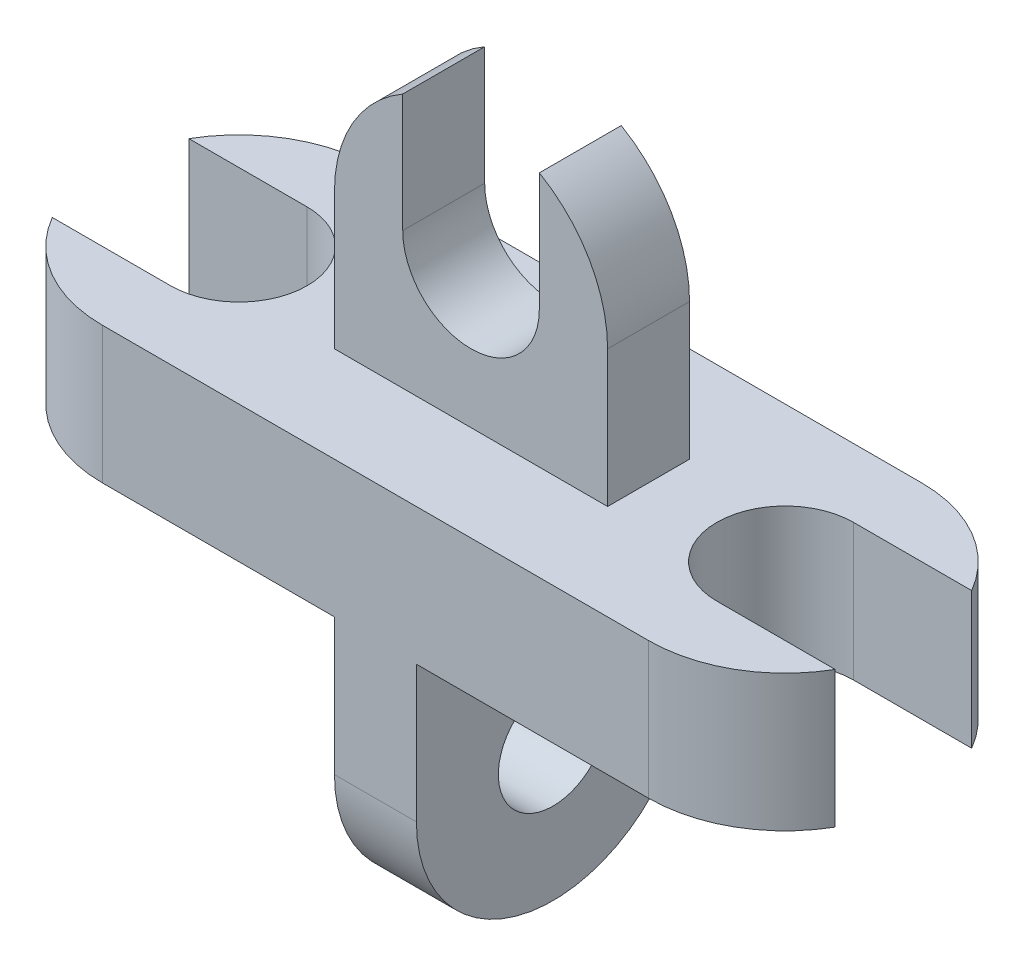
SolidWorks part; units mm, degrees
ref_plane "Front Plane" through (0, 0, 0) normal (0, 0, 1) x (1, 0, 0)
ref_plane "Top Plane" through (0, 0, 0) normal (0, 1, 0) x (1, 0, 0)
ref_plane "Right Plane" through (0, 0, 0) normal (1, 0, 0) x (0, 0, -1)
sketch "Sketch1" plane through (0, 0, 0) normal (0, 1, 0) x (1, 0, 0)
  line L0 (100, 0) -> (-100, 0) construction
  line L1 (100, -50) -> (-100, -50)
  line L2 (100, 50) -> (-100, 50)
  line L3 (-100, 25) -> (-143.3013, 25)
  line L4 (-100, -25) -> (-143.3013, -25)
  line L5 (0, 0) -> (0, 50) construction
  line L6 (100, -25) -> (143.3013, -25)
  line L7 (100, 25) -> (143.3013, 25)
  arc A1 (-100, 50) -> (-143.3013, 25) centre (-100, 0) ccw
  arc A2 (-100, -25) -> (-100, 25) centre (-100, 0) ccw
  arc A4 (-143.3013, -25) -> (-100, -50) centre (-100, 0) ccw
  arc A5 (143.3013, -25) -> (100, -50) centre (100, 0) cw
  arc A6 (100, -25) -> (100, 25) centre (100, 0) cw
  arc A7 (100, 50) -> (143.3013, 25) centre (100, 0) cw
  point P2 (0, 0)
  point P19 (0, 0)
  point P20 (0, 0)
  dimension "D1" = 50
  dimension "D3" = 200
  dimension "D2" = 25
extrude "Boss-Extrude1" add sketch "Sketch1" along normal mid plane 50
sketch "Sketch2" plane through (0, 0, 0) normal (0, 0, 1) x (1, 0, 0)
  line L0 (-100, 25) -> (100, 25) construction
  line L1 (-50, 75) -> (-50, 25)
  line L2 (50, 75) -> (50, 25)
  line L3 (-50, 25) -> (50, 25)
  line L4 (-25, 75) -> (-25, 118.3013)
  line L5 (25, 75) -> (25, 118.3013)
  arc A0 (50, 75) -> (25, 118.3013) centre (0, 75) ccw
  arc A1 (-25, 75) -> (25, 75) centre (0, 75) ccw
  arc A2 (-25, 118.3013) -> (-50, 75) centre (0, 75) ccw
  dimension "D1" = 100
  dimension "D2" = 50
  dimension "D3" = 50
extrude "Boss-Extrude2" add sketch "Sketch2" along normal mid plane 30
sketch "Sketch3" plane through (0, 0, 0) normal (1, 0, 0) x (0, 0, -1)
  line L0 (-50, -25) -> (-25, -25) construction
  line L1 (-50, -75) -> (-50, -25)
  line L2 (50, -75) -> (50, -25)
  line L3 (-50, -25) -> (50, -25)
  arc A0 (-50, -75) -> (50, -75) centre (0, -75) ccw
  circle A1 centre (0, -75) radius 20
  dimension "D1" = 100
  dimension "D2" = 50
  dimension "D3" = 40
extrude "Boss-Extrude3" add sketch "Sketch3" along normal mid plane 30
